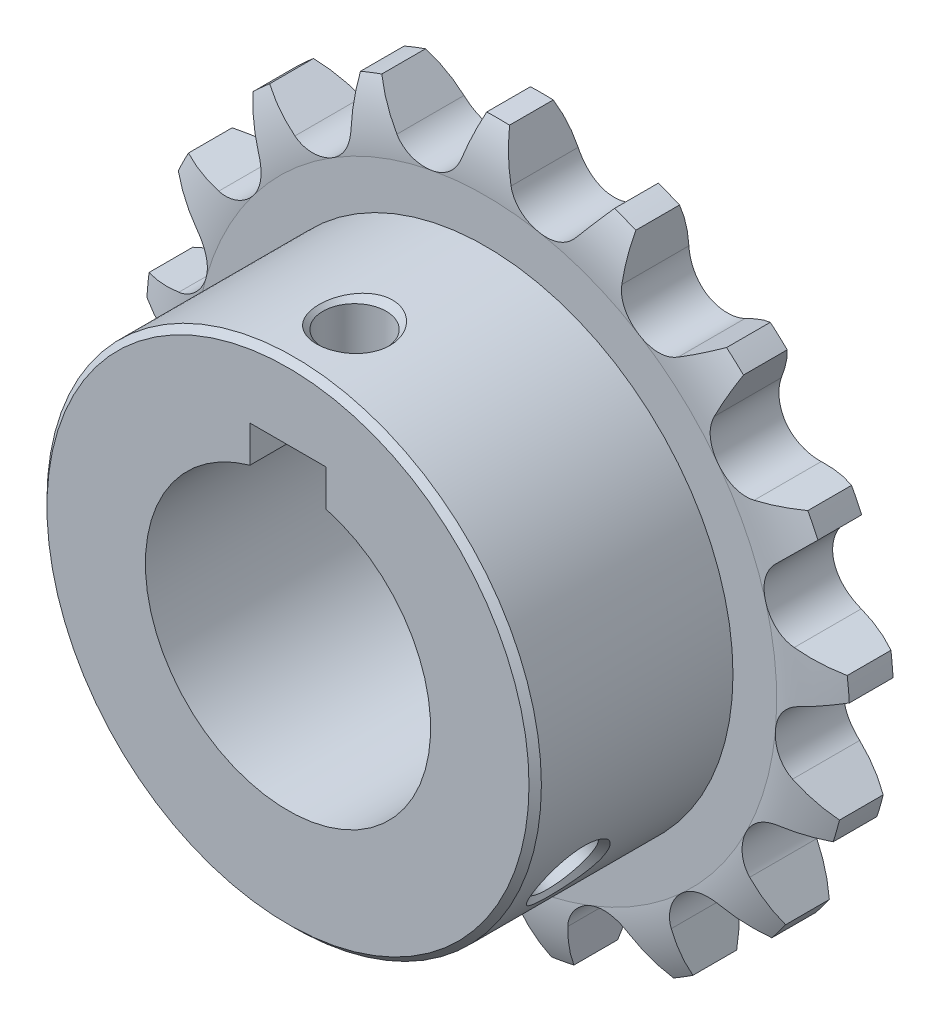
SolidWorks part; units mm, degrees
ref_plane "Front Plane" through (0, 0, 0) normal (0, 0, 1) x (1, 0, 0)
ref_plane "Top Plane" through (0, 0, 0) normal (0, 1, 0) x (1, 0, 0)
ref_plane "Right Plane" through (0, 0, 0) normal (1, 0, 0) x (0, 0, -1)
ref_plane "Plane1" through (0, 0, 0) normal (1, 0, 0) x (0, 0, -1)
sketch "Sketch1" plane through (0, 0, 0) normal (1, 0, 0) x (0, 0, -1)
  line L0 (-28, 25.35) -> (-28, 15)
  line L1 (-28, 15) -> (0, 15)
  line L2 (0, 15) -> (0, 30.6)
  line L3 (-1.3, 37) -> (-5.9, 37)
  line L4 (-7.2, 30.6) -> (-7.2, 26)
  line L5 (-7.2, 26) -> (-27.35, 26)
  line L6 (-27.35, 26) -> (-28, 25.35)
  line L7 (0, 0) -> (-3.6, 0) construction
  arc A0 (0, 30.6) -> (-1.3, 37) centre (-12.9814, 31.2952) ccw
  arc A1 (-5.9, 37) -> (-7.2, 30.6) centre (5.7814, 31.2952) ccw
revolve "Revolve1" add sketch "Sketch1" angle 360 about L7
ref_plane "Plane2" through (0, 0, 0) normal (0, 0, 1) x (1, 0, 0)
sketch "Sketch2" plane through (0, 0, 0) normal (0, 0, 1) x (1, 0, 0)
  line L0 (-36.9524, 2.2243) -> (-32.8375, 0.4471)
  line L1 (-32.1962, -6.4734) -> (-35.9145, -8.9764)
  line L2 (-35.9145, -8.9764) -> (-35.2606, -11.2747)
  line L3 (-35.2606, -11.2747) -> (-30.7816, -11.4454)
  line L4 (-27.6836, -17.6668) -> (-30.2466, -21.3441)
  line L5 (-30.2466, -21.3441) -> (-28.8067, -23.2509)
  line L6 (-28.8067, -23.2509) -> (-24.5684, -21.7921)
  line L7 (-19.4322, -26.4743) -> (-20.4938, -30.8291)
  line L8 (-20.4938, -30.8291) -> (-18.4622, -32.087)
  line L9 (-18.4622, -32.087) -> (-15.0372, -29.1956)
  line L10 (-8.5564, -31.7063) -> (-7.9731, -36.1505)
  line L11 (-7.9731, -36.1505) -> (-5.6243, -36.5895)
  line L12 (-5.6243, -36.5895) -> (-3.4751, -32.6562)
  line L13 (3.4751, -32.6562) -> (5.6243, -36.5895)
  line L14 (5.6243, -36.5895) -> (7.9731, -36.1505)
  line L15 (7.9731, -36.1505) -> (8.5564, -31.7063)
  line L16 (15.0372, -29.1956) -> (18.4622, -32.087)
  line L17 (18.4622, -32.087) -> (20.4938, -30.8291)
  line L18 (20.4938, -30.8291) -> (19.4322, -26.4743)
  line L19 (24.5684, -21.7921) -> (28.8067, -23.2509)
  line L20 (28.8067, -23.2509) -> (30.2466, -21.3441)
  line L21 (30.2466, -21.3441) -> (27.6836, -17.6668)
  line L22 (30.7816, -11.4454) -> (35.2606, -11.2747)
  line L23 (35.2606, -11.2747) -> (35.9145, -8.9764)
  line L24 (35.9145, -8.9764) -> (32.1962, -6.4734)
  line L25 (32.8375, 0.4471) -> (36.9524, 2.2243)
  line L26 (36.9524, 2.2243) -> (36.7319, 4.6036)
  line L27 (36.7319, 4.6036) -> (32.3605, 5.5944)
  line L28 (30.4585, 12.2792) -> (33.6536, 15.4228)
  line L29 (33.6536, 15.4228) -> (32.5885, 17.5618)
  line L30 (32.5885, 17.5618) -> (28.1544, 16.9066)
  line L31 (23.966, 22.4529) -> (25.8097, 26.5384)
  line L32 (25.8097, 26.5384) -> (24.0438, 28.1482)
  line L33 (24.0438, 28.1482) -> (20.1458, 25.9354)
  line L34 (14.2367, 29.5942) -> (14.48, 34.0699)
  line L35 (14.48, 34.0699) -> (12.2519, 34.9331)
  line L36 (12.2519, 34.9331) -> (9.4164, 31.4616)
  line L37 (2.5847, 32.7387) -> (1.1947, 37)
  line L38 (1.1947, 37) -> (-1.1947, 37)
  line L39 (-1.1947, 37) -> (-2.5847, 32.7387)
  line L40 (-9.4164, 31.4616) -> (-12.2519, 34.9331)
  line L41 (-12.2519, 34.9331) -> (-14.48, 34.0699)
  line L42 (-14.48, 34.0699) -> (-14.2367, 29.5942)
  line L43 (-20.1458, 25.9354) -> (-24.0438, 28.1482)
  line L44 (-24.0438, 28.1482) -> (-25.8097, 26.5384)
  line L45 (-25.8097, 26.5384) -> (-23.966, 22.4529)
  line L46 (-28.1544, 16.9066) -> (-32.5885, 17.5618)
  line L47 (-32.5885, 17.5618) -> (-33.6536, 15.4228)
  line L48 (-33.6536, 15.4228) -> (-30.4585, 12.2792)
  line L49 (-32.3605, 5.5944) -> (-36.7319, 4.6036)
  line L50 (-36.7319, 4.6036) -> (-36.9524, 2.2243)
  circle A0 centre (0, 0) radius 69.11
  arc A1 (-32.8375, 0.4471) -> (-32.1962, -6.4734) centre (-34.4076, -3.1883) cw
  arc A2 (-30.7816, -11.4454) -> (-27.6836, -17.6668) centre (-30.9324, -15.4025) cw
  arc A3 (-24.5684, -21.7921) -> (-19.4322, -26.4743) centre (-23.2796, -25.5365) cw
  arc A4 (-15.0372, -29.1956) -> (-8.5564, -31.7063) centre (-12.4827, -32.2216) cw
  arc A5 (-3.4751, -32.6562) -> (3.4751, -32.6562) centre (0, -34.555) cw
  arc A6 (8.5564, -31.7063) -> (15.0372, -29.1956) centre (12.4827, -32.2216) cw
  arc A7 (19.4322, -26.4743) -> (24.5684, -21.7921) centre (23.2796, -25.5365) cw
  arc A8 (27.6836, -17.6668) -> (30.7816, -11.4454) centre (30.9324, -15.4025) cw
  arc A9 (32.1962, -6.4734) -> (32.8375, 0.4471) centre (34.4076, -3.1883) cw
  arc A10 (32.3605, 5.5944) -> (30.4585, 12.2792) centre (33.2359, 9.4564) cw
  arc A11 (28.1544, 16.9066) -> (23.966, 22.4529) centre (27.5755, 20.824) cw
  arc A12 (20.1458, 25.9354) -> (14.2367, 29.5942) centre (18.1909, 29.3793) cw
  arc A13 (9.4164, 31.4616) -> (2.5847, 32.7387) centre (6.3495, 33.9666) cw
  arc A14 (-2.5847, 32.7387) -> (-9.4164, 31.4616) centre (-6.3495, 33.9666) cw
  arc A15 (-14.2367, 29.5942) -> (-20.1458, 25.9354) centre (-18.1909, 29.3793) cw
  arc A16 (-23.966, 22.4529) -> (-28.1544, 16.9066) centre (-27.5755, 20.824) cw
  arc A17 (-30.4585, 12.2792) -> (-32.3605, 5.5944) centre (-33.2359, 9.4564) cw
extrude "Cut-Extrude1" cut sketch "Sketch2" against normal blind 7.3 and the other way blind 7.3
ref_plane "Plane3" through (0, 0, 21) normal (0, 0, 1) x (1, 0, 0)
sketch "Sketch3" plane through (0, 0, 21) normal (0, 0, 1) x (1, 0, 0)
  line L0 (0, 14.5) -> (-3.3235, 14.5)
  line L1 (-3.3235, 14.5) -> (-3.3235, 25.3235)
  line L2 (-3.3235, 25.3235) -> (-4, 26)
  line L3 (-4, 26) -> (0, 26)
  line L4 (0, 26) -> (0, 14.5)
  line L5 (0, 26) -> (0, 14.5) construction
revolve "Cut-Revolve1" cut sketch "Sketch3" angle 360 about L5
cosmetic thread "Cosmetic Thread1" parameters "D1"=7.7, "D2"=8
ref_plane "Plane4" through (0, 0, 21) normal (0, 0, 1) x (1, 0, 0)
sketch "Sketch4" plane through (0, 0, 21) normal (0, 0, 1) x (1, 0, 0)
  line L0 (0, 0) -> (1.6618, 2.8782)
  line L1 (1.6618, 2.8782) -> (23.5925, -9.7835)
  line L2 (23.5925, -9.7835) -> (24.5167, -9.5359)
  line L3 (24.5167, -9.5359) -> (22.5167, -13)
  line L4 (22.5167, -13) -> (0, 0)
  line L5 (22.5167, -13) -> (0, 0) construction
revolve "Cut-Revolve2" cut sketch "Sketch4" angle 360 about L5
cosmetic thread "Cosmetic Thread2" parameters "D1"=11, "D2"=8
ref_plane "Plane5" through (0, 0, 0) normal (0, 0, 1) x (1, 0, 0)
sketch "Sketch5" plane through (0, 0, 0) normal (0, 0, 1) x (1, 0, 0)
  line L0 (-4, 18.3) -> (-4, 0)
  line L1 (-4, 0) -> (4, 0)
  line L2 (4, 0) -> (4, 18.3)
  line L3 (4, 18.3) -> (-4, 18.3)
extrude "Cut-Extrude2" cut sketch "Sketch5" along normal blind 28
ref_plane "Plane6" through (0, 0, 3.5) normal (0, 0, 1) x (1, 0, 0)
sketch "Sketch6" plane through (0, 0, 3.5) normal (0, 0, 1) x (1, 0, 0)
  circle A0 centre (0, 0) radius 34.2
